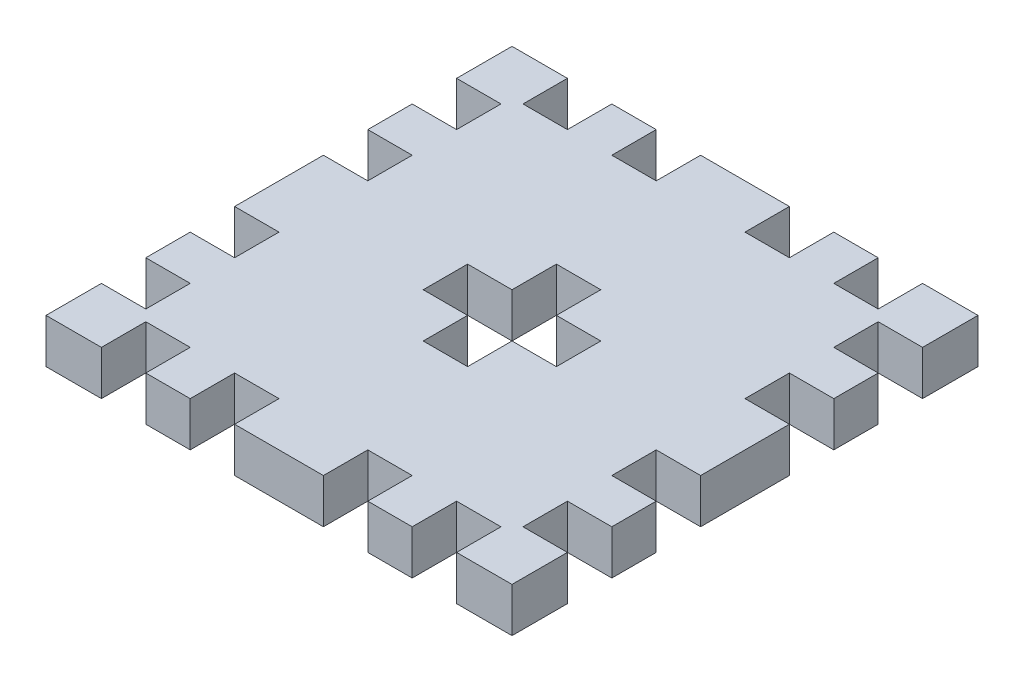
SolidWorks part; units mm, degrees
ref_plane "Front Plane" through (0, 0, 0) normal (0, 0, 1) x (1, 0, 0)
ref_plane "Top Plane" through (0, 0, 0) normal (0, 1, 0) x (1, 0, 0)
ref_plane "Right Plane" through (0, 0, 0) normal (1, 0, 0) x (0, 0, -1)
sketch "Sketch1" plane through (0, 0, 0) normal (0, 1, 0) x (1, 0, 0)
  line L1 (-22.5003, 17.6788) -> (30.8197, 17.6788)
  line L2 (-22.5003, 17.6788) -> (-22.5003, -35.6412)
  line L3 (-22.5003, -35.6412) -> (30.8197, -35.6412)
  line L4 (30.8197, 17.6788) -> (30.8197, -35.6412)
  dimension "D1" = 53.32
  dimension "D2" = 53.32
extrude "Boss-Extrude1" add sketch "Sketch1" along normal blind 5.08
sketch "Sketch2" plane through (0, 5.08, 0) normal (0, 1, 0) x (1, 0, 0)
  line L0 (4.1597, 17.6788) -> (4.1597, -35.6412) construction
  line L1 (30.8197, 17.6788) -> (-22.5003, 17.6788) construction
  line L2 (-22.5003, -35.6412) -> (30.8197, -35.6412) construction
  line L3 (-22.5003, -8.9812) -> (30.8197, -8.9812) construction
  line L4 (-22.5003, 17.6788) -> (-22.5003, -35.6412) construction
  line L5 (30.8197, -35.6412) -> (30.8197, 17.6788) construction
  line L6 (4.1597, -30.5612) -> (30.8197, -30.5612) construction
  line L7 (-16.1603, -30.5612) -> (-16.1603, -35.6412)
  line L8 (9.2397, -30.5612) -> (14.3197, -30.5612)
  line L9 (9.2397, -30.5612) -> (9.2397, -35.6412)
  line L10 (9.2397, -35.6412) -> (14.3197, -35.6412)
  line L11 (14.3197, -30.5612) -> (14.3197, -35.6412)
  line L12 (19.3997, -30.5612) -> (24.4797, -30.5612)
  line L13 (19.3997, -30.5612) -> (19.3997, -35.6412)
  line L14 (19.3997, -35.6412) -> (24.4797, -35.6412)
  line L15 (24.4797, -30.5612) -> (24.4797, -35.6412)
  line L16 (-11.0803, -35.6412) -> (-16.1603, -35.6412)
  line L17 (-11.0803, -30.5612) -> (-11.0803, -35.6412)
  line L18 (-11.0803, -30.5612) -> (-16.1603, -30.5612)
  line L19 (-6.0003, -30.5612) -> (-6.0003, -35.6412)
  line L20 (-0.9203, -35.6412) -> (-6.0003, -35.6412)
  line L21 (-0.9203, -30.5612) -> (-0.9203, -35.6412)
  line L22 (-0.9203, -30.5612) -> (-6.0003, -30.5612)
  line L23 (-17.4203, 11.3388) -> (-22.5003, 11.3388)
  line L24 (-17.4203, -14.0612) -> (-17.4203, -19.1412)
  line L25 (-17.4203, -14.0612) -> (-22.5003, -14.0612)
  line L26 (-22.5003, -14.0612) -> (-22.5003, -19.1412)
  line L27 (-17.4203, -19.1412) -> (-22.5003, -19.1412)
  line L28 (-17.4203, -24.2212) -> (-17.4203, -29.3012)
  line L29 (-17.4203, -24.2212) -> (-22.5003, -24.2212)
  line L30 (-22.5003, -24.2212) -> (-22.5003, -29.3012)
  line L31 (-17.4203, -29.3012) -> (-22.5003, -29.3012)
  line L32 (-22.5003, 6.2588) -> (-22.5003, 11.3388)
  line L33 (-17.4203, 6.2588) -> (-22.5003, 6.2588)
  line L34 (-17.4203, 6.2588) -> (-17.4203, 11.3388)
  line L35 (-17.4203, 1.1788) -> (-22.5003, 1.1788)
  line L36 (-22.5003, -3.9012) -> (-22.5003, 1.1788)
  line L37 (-17.4203, -3.9012) -> (-22.5003, -3.9012)
  line L38 (-17.4203, -3.9012) -> (-17.4203, 1.1788)
  line L39 (24.4797, 12.5988) -> (24.4797, 17.6788)
  line L40 (-0.9203, 12.5988) -> (-6.0003, 12.5988)
  line L41 (-0.9203, 12.5988) -> (-0.9203, 17.6788)
  line L42 (-0.9203, 17.6788) -> (-6.0003, 17.6788)
  line L43 (-6.0003, 12.5988) -> (-6.0003, 17.6788)
  line L44 (-11.0803, 12.5988) -> (-16.1603, 12.5988)
  line L45 (-11.0803, 12.5988) -> (-11.0803, 17.6788)
  line L46 (-11.0803, 17.6788) -> (-16.1603, 17.6788)
  line L47 (-16.1603, 12.5988) -> (-16.1603, 17.6788)
  line L48 (19.3997, 17.6788) -> (24.4797, 17.6788)
  line L49 (19.3997, 12.5988) -> (19.3997, 17.6788)
  line L50 (19.3997, 12.5988) -> (24.4797, 12.5988)
  line L51 (14.3197, 12.5988) -> (14.3197, 17.6788)
  line L52 (9.2397, 17.6788) -> (14.3197, 17.6788)
  line L53 (9.2397, 12.5988) -> (9.2397, 17.6788)
  line L54 (9.2397, 12.5988) -> (14.3197, 12.5988)
  line L55 (25.7397, -29.3012) -> (30.8197, -29.3012)
  line L56 (25.7397, -3.9012) -> (25.7397, 1.1788)
  line L57 (25.7397, -3.9012) -> (30.8197, -3.9012)
  line L58 (30.8197, -3.9012) -> (30.8197, 1.1788)
  line L59 (25.7397, 1.1788) -> (30.8197, 1.1788)
  line L60 (25.7397, 6.2588) -> (25.7397, 11.3388)
  line L61 (25.7397, 6.2588) -> (30.8197, 6.2588)
  line L62 (30.8197, 6.2588) -> (30.8197, 11.3388)
  line L63 (25.7397, 11.3388) -> (30.8197, 11.3388)
  line L64 (30.8197, -24.2212) -> (30.8197, -29.3012)
  line L65 (25.7397, -24.2212) -> (30.8197, -24.2212)
  line L66 (25.7397, -24.2212) -> (25.7397, -29.3012)
  line L67 (25.7397, -19.1412) -> (30.8197, -19.1412)
  line L68 (30.8197, -14.0612) -> (30.8197, -19.1412)
  line L69 (25.7397, -14.0612) -> (30.8197, -14.0612)
  line L70 (25.7397, -14.0612) -> (25.7397, -19.1412)
  point P30 (4.1597, -8.9812)
  point P82 (4.1597, -8.9812)
  dimension "D1" = 5.08
  dimension "D2" = 5.08
  dimension "D3" = 5.08
  dimension "D4" = 5.08
  dimension "D5" = 5.08
  dimension "D6" = 4
extrude "Cut-Extrude1" cut sketch "Sketch2" against normal blind 5.08
sketch "Sketch3" plane through (0, 5.08, 0) normal (0, 1, 0) x (1, 0, 0)
  line L0 (4.1597, 17.6788) -> (4.1597, -35.6412) construction
  line L1 (9.2397, 17.6788) -> (-0.9203, 17.6788) construction
  line L2 (-0.9203, -35.6412) -> (9.2397, -35.6412) construction
  line L3 (30.8197, -8.9812) -> (-22.5003, -8.9812) construction
  line L4 (30.8197, -14.0612) -> (30.8197, -3.9012) construction
  line L5 (-22.5003, -3.9012) -> (-22.5003, -14.0612) construction
  line L6 (4.1597, -1.3612) -> (6.6997, -1.3612)
  line L7 (6.6997, -1.3612) -> (6.6997, -6.4412)
  line L8 (6.6997, -6.4412) -> (11.7797, -6.4412)
  line L9 (11.7797, -6.4412) -> (11.7797, -8.9812)
  line L10 (11.7797, -8.9812) -> (11.7797, -11.5212)
  line L11 (11.7797, -11.5212) -> (6.6997, -11.5212)
  line L12 (6.6997, -11.5212) -> (6.6997, -16.6012)
  line L13 (6.6997, -16.6012) -> (4.1597, -16.6012)
  line L14 (4.1597, -16.6012) -> (1.6197, -16.6012)
  line L15 (1.6197, -16.6012) -> (1.6197, -11.5212)
  line L16 (1.6197, -11.5212) -> (-3.4603, -11.5212)
  line L17 (-3.4603, -11.5212) -> (-3.4603, -8.9812)
  line L18 (-3.4603, -8.9812) -> (-3.4603, -6.4412)
  line L19 (-3.4603, -6.4412) -> (1.6197, -6.4412)
  line L20 (1.6197, -6.4412) -> (1.6197, -1.3612)
  line L21 (1.6197, -1.3612) -> (4.1597, -1.3612)
  point P14 (4.1597, -8.9812)
  point P36 (4.1597, -8.9812)
  dimension "D1" = 2.54
  dimension "D2" = 5.08
  dimension "D3" = 2.54
  dimension "D4" = 5.08
  dimension "D5" = 4
extrude "Cut-Extrude2" cut sketch "Sketch3" against normal blind 5.08
